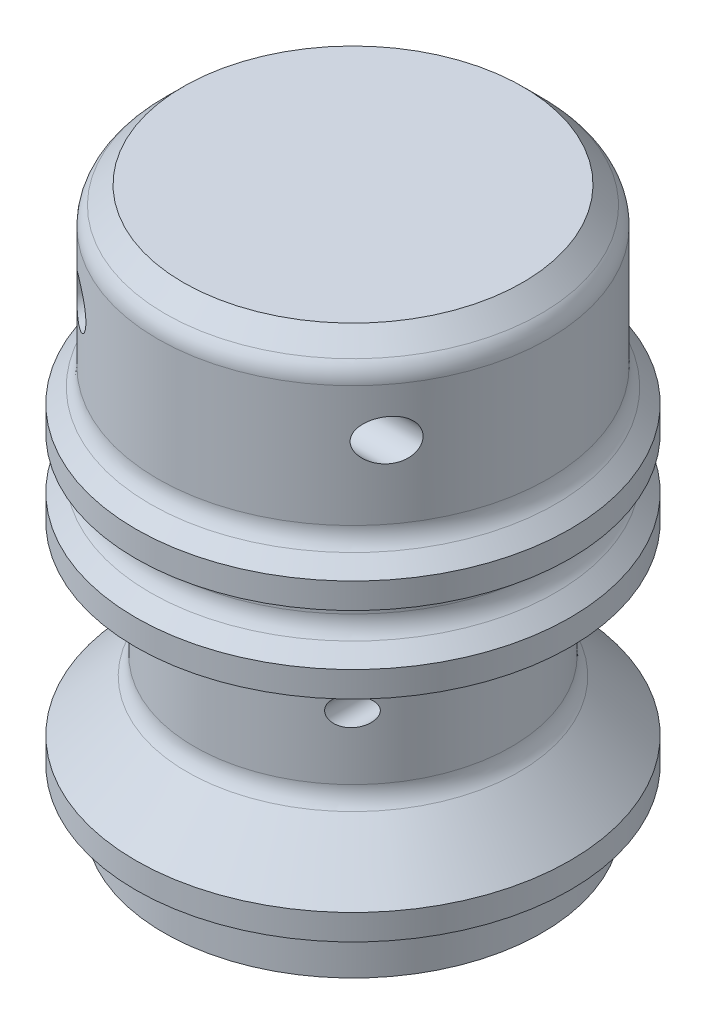
SolidWorks part; units mm, degrees
ref_plane "Plano frontal" through (0, 0, 0) normal (0, 0, 1) x (1, 0, 0)
ref_plane "Plano superior" through (0, 0, 0) normal (0, 1, 0) x (1, 0, 0)
ref_plane "Plano direito" through (0, 0, 0) normal (1, 0, 0) x (0, 0, -1)
sketch "Cut_1" plane through (0, 0, 0) normal (0, 1, 0) x (1, 0, 0)
  line L0 (4.658, 6.0576) -> (4.658, 2.8486) construction
  line L1 (3.856, 3.8656) -> (3.856, 6.5972)
  line L2 (5.46, 0) -> (5.46, 5.346)
  line L3 (3.856, 3.8656) -> (4.658, 3.8656) construction
  line L4 (4.658, 3.8656) -> (5.46, 3.8656) construction
  circle A0 centre (0, 0) radius 5.46
  circle A2 centre (0, 0) radius 7.6414
  circle A4 centre (0, 0) radius 3.105
  dimension "D1" = 10.92
  dimension "D5" = 15.2829
  dimension "D6" = 6.21
  dimension "D2" = 4.658
  dimension "D3" = 1.604
  dimension "D4" = 3.209
  dimension "D7" = 0.802
sketch "Cut_2" plane through (0, 0, 0) normal (0, 1, 0) x (1, 0, 0)
  line L0 (4.889, 0) -> (4.889, 3.8203)
  line L1 (3.797, 3.0798) -> (3.797, 4.9071)
  line L2 (3.797, 3.0798) -> (4.343, 3.0798) construction
  line L3 (4.343, 3.0798) -> (4.889, 3.0798) construction
  line L4 (4.343, 4.4311) -> (4.343, 2.2451) construction
  circle A0 centre (0, 0) radius 4.889
  circle A1 centre (0, 0) radius 6.2046
  circle A2 centre (0, 0) radius 4.889
  circle A3 centre (0, 0) radius 5.798
  dimension "D1" = 9.778
  dimension "D2" = 4.343
  dimension "D5" = 12.4091
  dimension "D6" = 9.778
  dimension "D7" = 11.596
  dimension "D3" = 1.092
  dimension "D4" = 2.186
  dimension "D8" = 0.546
sketch "Esboço4" plane through (0, 0, 0) normal (0, 0, 1) x (1, 0, 0)
  line L0 (0, 0) -> (0, 9.8449) construction
  line L1 (4.889, 0) -> (4.889, 4.889) construction
  line L2 (3.105, 1) -> (3.105, 10.329)
  line L3 (3.105, 10.329) -> (5.46, 12.684)
  line L4 (5.46, 12.684) -> (5.46, 19.658)
  line L5 (5.46, 19.658) -> (0, 19.658)
  line L6 (0, 19.658) -> (0, 21.658)
  line L7 (0, 21.658) -> (7.6414, 21.658)
  line L8 (7.6414, 21.658) -> (7.6414, 10.732)
  line L9 (7.6414, 10.732) -> (6.2046, 10.732)
  line L10 (6.2046, 10.732) -> (6.2046, 4)
  line L11 (6.2046, 4) -> (7.4, 4)
  line L12 (7.4, 4) -> (7.4, 0)
  line L13 (7.4, 0) -> (5.798, 0)
  line L14 (4.889, 4.4734) -> (4.889, 4.889)
  line L16 (4.889, 4.889) -> (4.889, 9.232)
  line L17 (4.889, 9.232) -> (4.105, 9.232)
  line L18 (4.105, 9.232) -> (4.105, 1)
  line L19 (4.105, 1) -> (3.105, 1)
  line L21 (6.2046, 4) -> (6.2046, 0) construction
  line L22 (5.798, 0) -> (5.798, 2.899)
  line L23 (4.889, 0) -> (-4.889, 0) construction
  line L24 (5.798, 2.899) -> (4.889, 4.4734)
  line L25 (5.46, 12.684) -> (5.46, 0) construction
  line L26 (3.105, 1) -> (3.105, 0) construction
  line L28 (7.6414, 10.732) -> (7.6414, 0) construction
  line L29 (4.889, 4.4734) -> (4.889, 0) construction
  line L32 (0, 9.232) -> (4.28, 9.232) construction
  dimension "D1" = 1
  dimension "D2" = 14.8
  dimension "D3" = 1
  dimension "D4" = 4
  dimension "D5" = 45
  dimension "D6" = 9.329
  dimension "D7" = 4.343
  dimension "D8" = 2
  dimension "D9" = 30
  dimension "D10" = 9.329
  dimension "D11" = 1.5
  dimension "D12" = 4.889
  dimension "D13" = 1.1954
  dimension "D14" = 4.28
  dimension "D16" = 2.899
revolve "Revolução1" add sketch "Esboço4" angle 360 about L0
sketch "Esboço5" plane through (0, 0, 0) normal (0, 0, 1) x (1, 0, 0)
  line L0 (0, 0) -> (0, 18.356) construction
  line L1 (4.889, 0) -> (-4.889, 0) construction
  line L2 (0, 18.356) -> (0, 19.658) construction
  line L3 (0, 18.356) -> (4.658, 18.356) construction
  line L4 (4.658, 18.356) -> (4.658, 0) construction
  line L5 (-5.46, 19.658) -> (5.46, 19.658) construction
  line L6 (-4.105, 0) -> (-4.105, 8.186) construction
  line L7 (5.46, 0) -> (-5.46, 0) construction
  line L8 (-4.105, 8.186) -> (-4.105, 9.232) construction
  line L9 (-4.105, 8.186) -> (-4.343, 8.186) construction
  line L10 (-4.343, 8.186) -> (-4.343, 0) construction
  line L15 (-4.343, 0) -> (0, 0) construction
  line L16 (0, 0) -> (4.343, 0) construction
  line L17 (4.889, 0) -> (-4.889, 0) construction
  circle A0 centre (4.658, 18.356) radius 0.802
  circle A1 centre (-4.343, 8.186) radius 0.546
  point P2 (0, 0)
  point P13 (4.105, 8.186)
  point P26 (0, 0)
  point P27 (-3.4444, 7.8689)
  point P28 (0, 0)
  dimension "D1" = 1.604
  dimension "D3" = 1.092
  dimension "D2" = 1.302
  dimension "D4" = 1.046
extrude "Inlet_1" cut sketch "Esboço5" against normal through all contours A0
pattern_circular "PadrãoCircular1" count 4 over 360 about axis through (0, 0, 0) along (0, -1, 0) of "Inlet_1"
ref_plane "Plano1" through (0, 0, -10) normal (0, 0, 1) x (1, 0, 0)
sketch "Esboço9" plane through (0, 0, -10) normal (0, 0, 1) x (1, 0, 0)
  circle A0 centre (-4.343, 8.186) radius 0.546
  circle A1 centre (-4.343, 8.186) radius 0.546 construction
extrude "Corte-extrusão1" cut sketch "Esboço9" along normal up to surface (6.9202 mm away) contours A0
pattern_circular "PadrãoCircular2" count 4 over 360 of "Corte-extrusão1"
chamfer "Chanfro1" distance 1 angle 45 1 edges at (0, 21.658, -7.6414)
fillet "Filete3" radius 1 1 edges at (0, 20.658, 7.6414)
fillet "Filete_topo" radius 0.35 3 edges at (0, 9.232, -4.105) (0, 9.232, -4.889) (0, 19.658, -5.46)
fillet "Filete_base" radius 2 4 edges at (0, 10.329, -3.105) (0, 12.684, -5.46) (0, 4.4734, -4.889) (0, 2.899, -5.798)
sketch "Esboço11" plane through (0, 0, 0) normal (0, 0, 1) x (1, 0, 0)
  line L0 (6.2046, 10.232) -> (8.5, 10.232)
  line L1 (8.5, 10.232) -> (8.5, 11.232)
  line L2 (8.5, 11.232) -> (7.6414, 12.0906)
  line L3 (7.6414, 12.0906) -> (7.6414, 13.232)
  line L4 (7.6414, 13.232) -> (8.5, 13.232)
  line L5 (8.5, 13.232) -> (8.5, 14.232)
  line L6 (8.5, 14.232) -> (7.6414, 15.0906)
  line L7 (7.6414, 15.0906) -> (7.1414, 15.0906)
  line L8 (7.1414, 15.0906) -> (7.1414, 11.232)
  line L9 (7.1414, 11.232) -> (5.7046, 11.232)
  line L10 (5.7046, 11.232) -> (5.7046, 10.232)
  line L11 (5.7046, 10.232) -> (6.2046, 10.232)
  line L12 (7.4, 2) -> (8.5, 2)
  line L13 (8.5, 2) -> (8.5, 3)
  line L14 (8.5, 3) -> (6.2046, 5.2954)
  line L15 (6.2046, 5.2954) -> (5.7046, 5.2954)
  line L16 (5.7046, 5.2954) -> (5.7046, 4)
  line L17 (5.7046, 4) -> (6.9, 2)
  line L18 (6.9, 2) -> (7.4, 2)
  line L19 (7.6414, 15.0906) -> (7.6414, 10.732) construction
  line L20 (5.7046, 4) -> (6.2046, 4) construction
  line L22 (6.2046, 10.232) -> (6.2046, 10.732) construction
  line L23 (6.2046, 10.732) -> (6.2046, 11.232) construction
  line L26 (0, 0) -> (0, 7.0334) construction
  line L27 (7.4, 2) -> (7.4, 0) construction
  line L30 (6.2046, 5.2954) -> (6.2046, 4) construction
  dimension "D1" = 0.5
  dimension "D2" = 0.5
  dimension "D3" = 1
  dimension "D4" = 4
  dimension "D5" = 45
  dimension "D6" = 0.5
  dimension "D7" = 0.5
  dimension "D8" = 17
  dimension "D9" = 0.5
  dimension "D10" = 2
  dimension "D11" = 0.5
  dimension "D12" = 45
  dimension "D13" = 1
  dimension "D15" = 0.8586
  dimension "D16" = 1.1414
revolve "Revolução2" add sketch "Esboço11" angle 360 about L26
fillet "Filete4" radius 1 4 edges at (0, 12.0906, -7.6414) (0, 15.0906, 7.6414) (0, 5.2954, 6.2046) (0, 10.232, -6.2046)
fillet "Filete5" radius 0.5 2 edges at (0, 2, -7.4) (0, 13.232, -7.6414)
equation "\"D2@Esboço5\"=\"D1@Esboço5\"/2+0.5"
equation "\"D4@Esboço5\"=\"D3@Esboço5\"/2+0.5"
